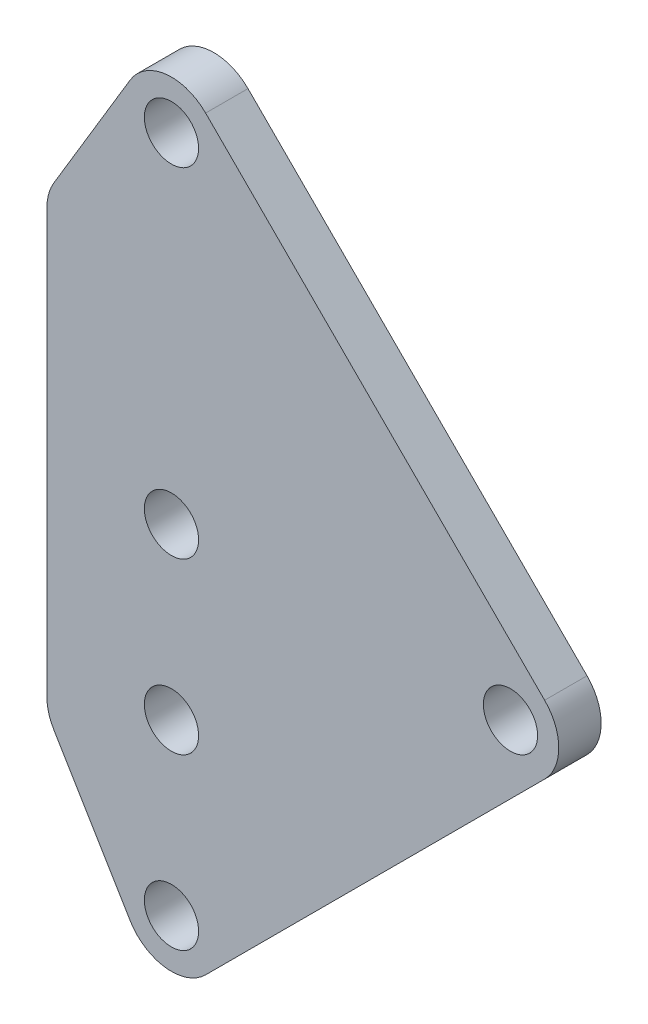
SolidWorks part; units mm, degrees
ref_plane "Front Plane" through (0, 0, 0) normal (0, 0, 1) x (1, 0, 0)
ref_plane "Top Plane" through (0, 0, 0) normal (0, 1, 0) x (1, 0, 0)
ref_plane "Right Plane" through (0, 0, 0) normal (1, 0, 0) x (0, 0, -1)
sketch "Sketch1" plane through (0, 0, 0) normal (0, 0, 1) x (1, 0, 0)
  line L3 (2.5594, 27.9594) -> (27.9594, 2.5594)
  line L5 (2.5594, -27.9594) -> (27.9594, -2.5594)
  line L6 (-9.331, -16.3465) -> (-9.331, 26.4535) construction
  line L7 (-9.331, 15.875) -> (-9.331, -15.875)
  line L8 (-3.1042, -27.2614) -> (-8.8157, -17.7364)
  line L9 (-3.1042, 27.2614) -> (-8.8157, 17.7364)
  circle A0 centre (0, 0) radius 2.032
  circle A1 centre (0, 25.4) radius 2.032
  circle A2 centre (0, -25.4) radius 2.032
  circle A3 centre (25.4, 0) radius 2.032
  arc A4 (2.5594, 27.9594) -> (-3.1042, 27.2614) centre (0, 25.4) ccw
  arc A5 (-3.1042, -27.2614) -> (2.5594, -27.9594) centre (0, -25.4) ccw
  arc A6 (27.9594, -2.5594) -> (27.9594, 2.5594) centre (25.4, 0) ccw
  arc A7 (-9.331, -15.875) -> (-8.8157, -17.7364) centre (-5.7115, -15.875) ccw
  arc A9 (-8.8157, 17.7364) -> (-9.331, 15.875) centre (-5.7115, 15.875) ccw
  circle A11 centre (0, -12.7) radius 2.032
  point P10 (0, -12.7)
  dimension "D3" = 7.239
  dimension "D4" = 4.064
  dimension "D6" = 7.239
  dimension "D1" = 25.4
  dimension "D2" = 25.4
  dimension "D5" = 25.4
  dimension "D7" = 9.525
  dimension "D8" = 9.525
  dimension "D9" = 12.7
extrude "Boss-Extrude1" add sketch "Sketch1" along normal blind 3.175
